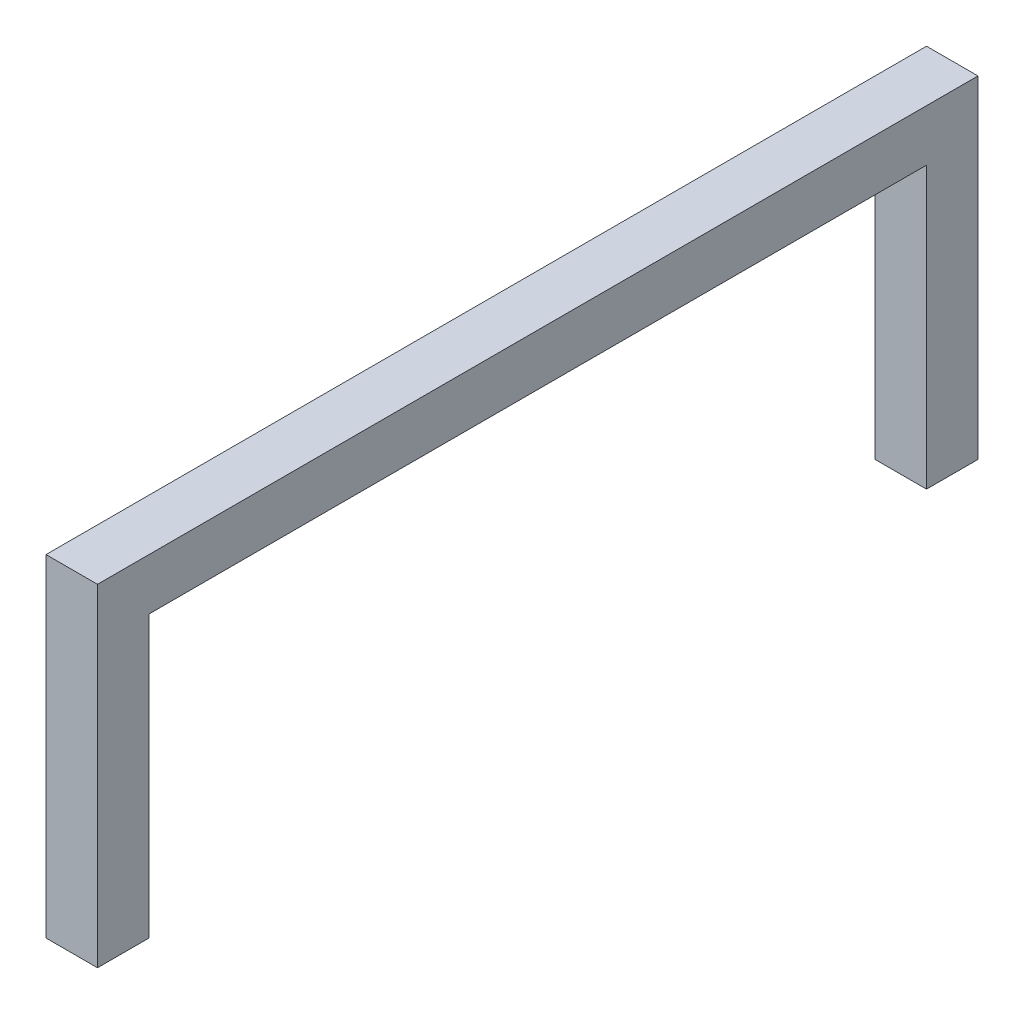
SolidWorks part; units mm, degrees
ref_plane "Front Plane" through (0, 0, 0) normal (0, 0, 1) x (1, 0, 0)
ref_plane "Top Plane" through (0, 0, 0) normal (0, 1, 0) x (1, 0, 0)
ref_plane "Right Plane" through (0, 0, 0) normal (1, 0, 0) x (0, 0, -1)
sketch "Sketch1" plane through (0, 0, 0) normal (1, 0, 0) x (0, 0, -1)
  line L0 (332.1814, 0) -> (-332.1814, 0) construction
  line L1 (0, 242.5595) -> (0, -242.5595) construction
  line L3 (-151, -54.5) -> (-171, -54.5)
  line L4 (-151, -54.5) -> (-151, 54.5)
  line L5 (0, 74.5) -> (-171, 74.5)
  line L6 (-171, -54.5) -> (-171, 74.5)
  line L7 (-171, 74.5) -> (171, 74.5)
  line L8 (-171, 74.5) -> (-171, -54.5)
  line L9 (-151, 54.5) -> (151, 54.5)
  line L10 (171, 74.5) -> (171, -54.5)
  line L11 (171, 74.5) -> (0, 74.5)
  line L12 (171, 74.5) -> (171, -54.5)
  line L13 (171, -54.5) -> (151, -54.5)
  line L14 (151, 54.5) -> (151, -54.5)
  point P2 (0, 74.5)
  point P5 (0, 0)
  point P8 (0, 0)
  point P12 (-148.8528, 74.5)
  point P13 (0, 0)
  point P17 (-171, -51.073)
  point P20 (171, -52.2594)
  point P21 (0, 0)
  point P22 (-171, -57.1747)
  point P23 (0, 0)
  dimension "D1" = 20
  dimension "D2" = 20
  dimension "D3" = 20
  dimension "D4" = 302
  dimension "D5" = 109
  dimension "D6" = 151
  dimension "D7" = 54.5
extrude "Boss-Extrude1" add sketch "Sketch1" along normal mid plane 20 contours L9 L14 L13 L10 L7 L5 L6 L3 L4
